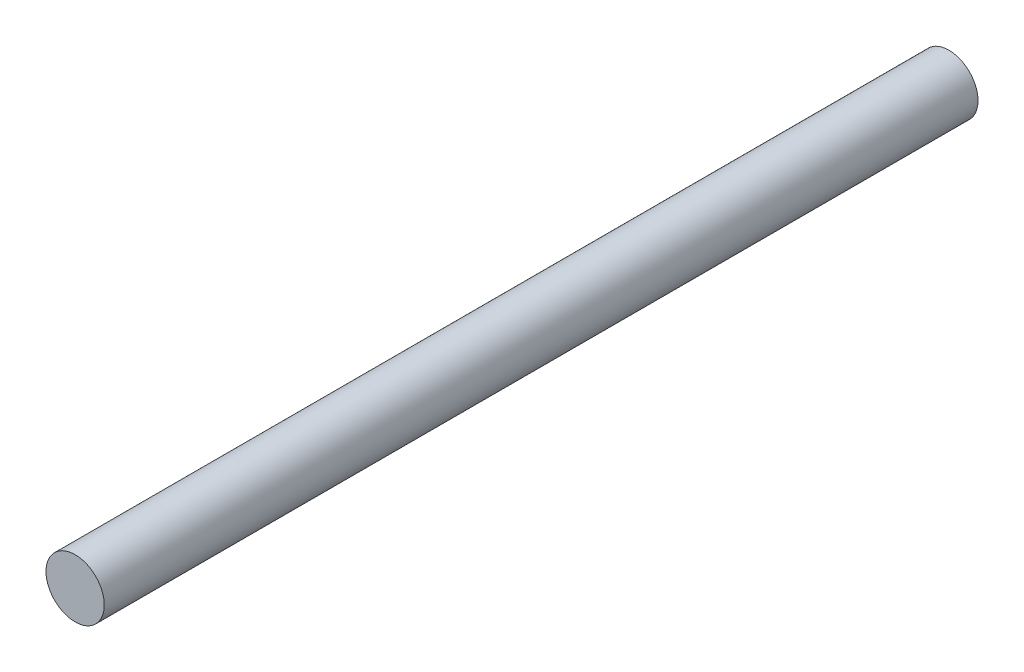
SolidWorks part; units mm, degrees
ref_plane "正面" through (0, 0, 0) normal (0, 0, 1) x (1, 0, 0)
ref_plane "平面" through (0, 0, 0) normal (0, 1, 0) x (1, 0, 0)
ref_plane "右側面" through (0, 0, 0) normal (1, 0, 0) x (0, 0, -1)
sketch "ｽｹｯﾁ1" plane through (0, 0, 0) normal (0, 0, 1) x (1, 0, 0)
  circle A0 centre (0, 0) radius 1.5
  dimension "D1" = 3
extrude "ﾎﾞｽ - 押し出し1" add sketch "ｽｹｯﾁ1" along normal blind 45
